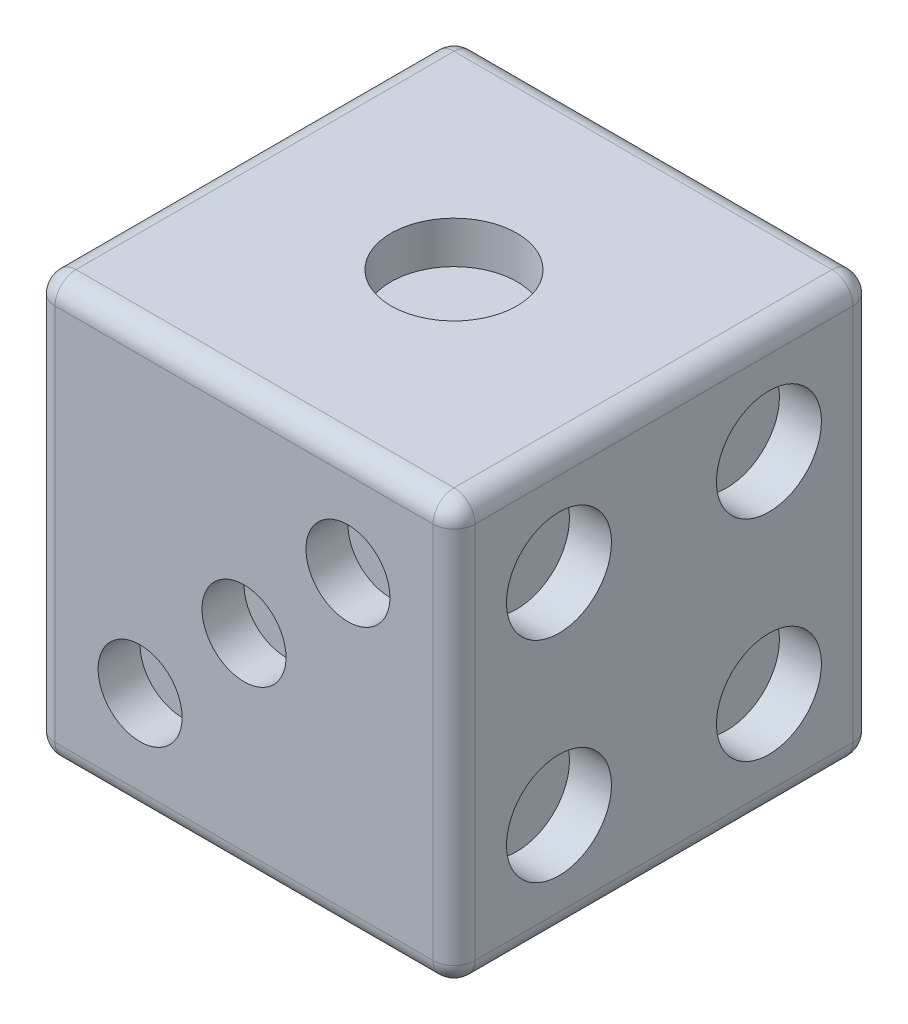
SolidWorks part; units mm, degrees
ref_plane "Front Plane" through (0, 0, 0) normal (0, 0, 1) x (1, 0, 0)
ref_plane "Top Plane" through (0, 0, 0) normal (0, 1, 0) x (1, 0, 0)
ref_plane "Right Plane" through (0, 0, 0) normal (1, 0, 0) x (0, 0, -1)
sketch "Sketch1" plane through (0, 0, 0) normal (0, 1, 0) x (1, 0, 0)
  line L5 (50, -50) -> (-50, -50)
  line L6 (50, -50) -> (50, 50)
  line L7 (50, 50) -> (-50, 50)
  line L8 (-50, -50) -> (-50, 50)
  line L9 (50, -50) -> (-50, 50) construction
  line L10 (50, 50) -> (-50, -50) construction
  point P0 (0, 0)
  dimension "D1" = 100
  dimension "D2" = 100
  dimension "D3" = 50
  dimension "D4" = 50
extrude "Boss-Extrude1" add sketch "Sketch1" along normal blind 100 contours L8 L7 L6 L5
sketch "Sketch3" plane through (0, 100, 0) normal (0, 1, 0) x (1, 0, 0)
  circle A0 centre (0, 0) radius 15
  dimension "D1" = 30
extrude "Cut-Extrude1" cut sketch "Sketch3" against normal blind 10 contours A0
sketch "Sketch5" plane through (0, 0, 50) normal (0, 0, 1) x (1, 0, 0)
  line L0 (50, 100) -> (-50, 0) construction
  circle A0 centre (0, 50) radius 10
  circle A1 centre (24.7487, 74.7487) radius 10
  circle A2 centre (-24.7487, 25.2513) radius 10
  dimension "D1" = 35
  dimension "D2" = 35
extrude "Cut-Extrude2" cut sketch "Sketch5" against normal blind 10 contours A1 | A0 | A2
sketch "Sketch8" plane through (-50, 0, 0) normal (-1, 0, 0) x (0, 0, 1)
  line L0 (-50, 100) -> (50, 0) construction
  circle A0 centre (-16.9706, 66.9706) radius 13
  circle A1 centre (16.9706, 33.0294) radius 13
  point P8 (0, 50)
  dimension "D1" = 48
  dimension "D2" = 24
extrude "Cut-Extrude3" cut sketch "Sketch8" against normal blind 10 contours A1 | A0
sketch "Sketch12" plane through (50, 0, 0) normal (1, 0, 0) x (0, 0, -1)
  line L0 (-50, 100) -> (50, 0) construction
  line L1 (50, 0) -> (50, 100) construction
  line L2 (50, 100) -> (-50, 0) construction
  line L3 (-50, 0) -> (-50, 100) construction
  line L5 (25, 25) -> (-25, 25) construction
  line L6 (25, 25) -> (25, 75) construction
  line L7 (25, 75) -> (-25, 75) construction
  line L8 (-25, 25) -> (-25, 75) construction
  line L9 (25, 25) -> (-25, 75) construction
  line L10 (25, 75) -> (-25, 25) construction
  circle A0 centre (-25, 75) radius 12.5
  circle A1 centre (25, 75) radius 12.5
  circle A2 centre (25, 25) radius 12.5
  circle A3 centre (-25, 25) radius 12.5
  point P8 (0, 50)
  dimension "D3" = 25
  dimension "D1" = 50
  dimension "D2" = 50
extrude "Cut-Extrude4" cut sketch "Sketch12" against normal blind 10 contours A2 | A1 | A0 | A3
sketch "Sketch13" plane through (0, 0, -50) normal (0, 0, -1) x (-1, 0, 0)
  line L0 (-50, 100) -> (50, 0) construction
  line L1 (50, 0) -> (50, 100) construction
  line L2 (50, 100) -> (-50, 0) construction
  line L3 (-50, 0) -> (-50, 100) construction
  line L5 (27.5, 22.5) -> (-27.5, 22.5) construction
  line L6 (27.5, 22.5) -> (27.5, 77.5) construction
  line L7 (27.5, 77.5) -> (-27.5, 77.5) construction
  line L8 (-27.5, 22.5) -> (-27.5, 77.5) construction
  line L9 (27.5, 22.5) -> (-27.5, 77.5) construction
  line L10 (27.5, 77.5) -> (-27.5, 22.5) construction
  circle A0 centre (0, 50) radius 10
  circle A1 centre (-27.5, 77.5) radius 10
  circle A2 centre (27.5, 77.5) radius 10
  circle A3 centre (27.5, 22.5) radius 10
  circle A4 centre (-27.5, 22.5) radius 10
  point P8 (0, 50)
  dimension "D1" = 55
extrude "Cut-Extrude5" cut sketch "Sketch13" against normal blind 10
sketch "Sketch14" plane through (0, 0, 0) normal (0, -1, 0) x (-1, 0, 0)
  line L0 (-16.67, 50) -> (-16.67, -50) construction
  line L1 (-50, 50) -> (50, 50) construction
  line L2 (-50, -50) -> (50, -50) construction
  line L3 (-50, -50) -> (-50, 50) construction
  line L4 (16.67, 50) -> (16.67, -50) construction
  line L5 (50, -50) -> (50, 50) construction
  line L6 (-50, -25) -> (50, -25) construction
  line L7 (-50, 25) -> (50, 25) construction
  line L8 (-50, 0) -> (50, 0) construction
  circle A0 centre (-16.67, 0) radius 10
  circle A1 centre (16.67, 0) radius 10
  circle A2 centre (16.67, 25) radius 10
  circle A3 centre (-16.67, 25) radius 10
  circle A4 centre (-16.67, -25) radius 10
  circle A5 centre (16.67, -25) radius 10
  dimension "D1" = 33.33
  dimension "D2" = 33.33
  dimension "D3" = 25
  dimension "D4" = 25
  dimension "D5" = 25
  dimension "D6" = 25
extrude "Cut-Extrude6" cut sketch "Sketch14" against normal blind 10
fillet "Fillet6" radius 5 12 edges at (0, 0, -50) (50, 50, -50) (50, 100, 0) (0, 100, -50) (50, 0, 0) (50, 50, 50) (0, 100, 50) (0, 0, 50) (-50, 50, 50) (-50, 100, 0) (-50, 50, -50) (-50, 0, 0)
